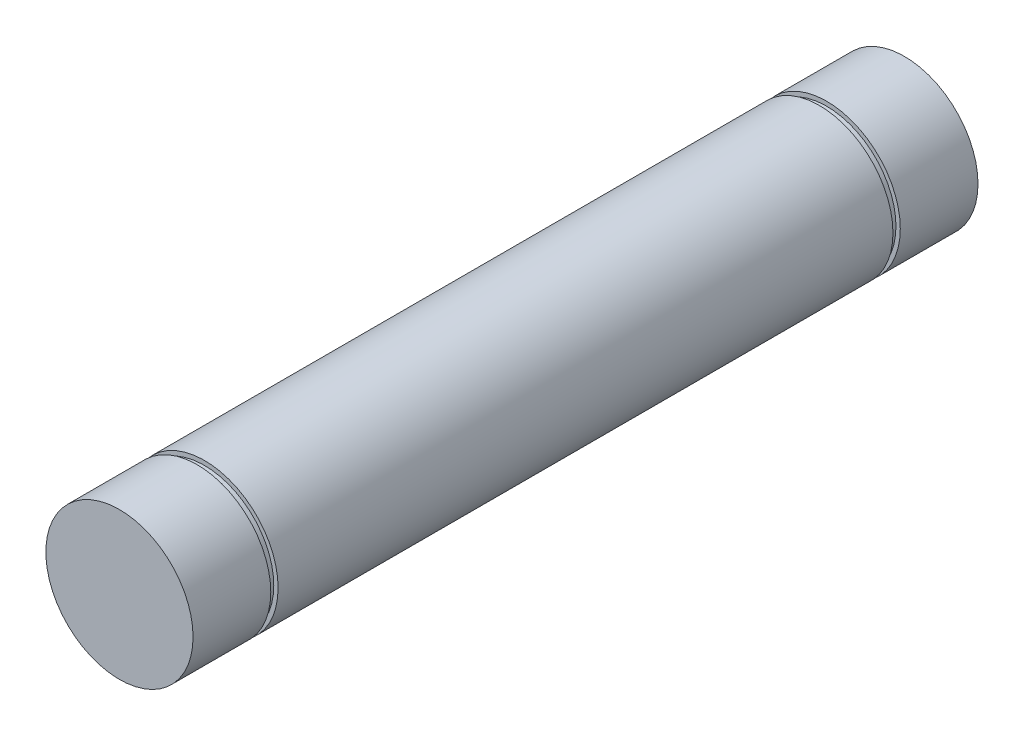
SolidWorks part; units mm, degrees
material "AISI 1020"
ref_plane "Front Plane" through (0, 0, 0) normal (0, 0, 1) x (1, 0, 0)
ref_plane "Top Plane" through (0, 0, 0) normal (0, 1, 0) x (1, 0, 0)
ref_plane "Right Plane" through (0, 0, 0) normal (1, 0, 0) x (0, 0, -1)
sketch "Sketch1" plane through (0, 0, 0) normal (0, 0, 1) x (1, 0, 0)
  circle A0 centre (0, 0) radius 14.29
  dimension "D1" = 28.5801
extrude "Boss-Extrude1" add sketch "Sketch1" against normal mid plane 152.4
ref_plane "Plane1" through (0, 0, 59.69) normal (0, 0, 1) x (1, 0, 0)
ref_plane "Plane2" through (0, 0, -59.69) normal (0, 0, 1) x (1, 0, 0)
sketch "Sketch2" plane through (0, 0, 0) normal (1, 0, 0) x (0, 0, -1)
  line L0 (76.2, 14.29) -> (-76.2, 14.29) construction
  line L1 (-61.1124, 14.29) -> (-59.69, 14.29)
  line L2 (-61.1124, 14.29) -> (-61.1124, 13.4493)
  line L3 (-61.1124, 13.4493) -> (-59.69, 13.4493)
  line L4 (-59.69, 14.29) -> (-59.69, 13.4493)
  line L5 (-59.69, 15.7805) -> (-59.69, -15.7805) construction
  line L6 (-76.2, 0) -> (-64.9522, 0) construction
  line L7 (-76.2, 14.29) -> (-76.2, -14.29) construction
  dimension "D1" = 1.4224
  dimension "D2" = 26.8986
revolve "Cut-Revolve1" cut sketch "Sketch2" angle 360 about L6
mirror "Mirror1" about plane through (0, 0, 0) normal (0, 0, 1) of "Cut-Revolve1"
